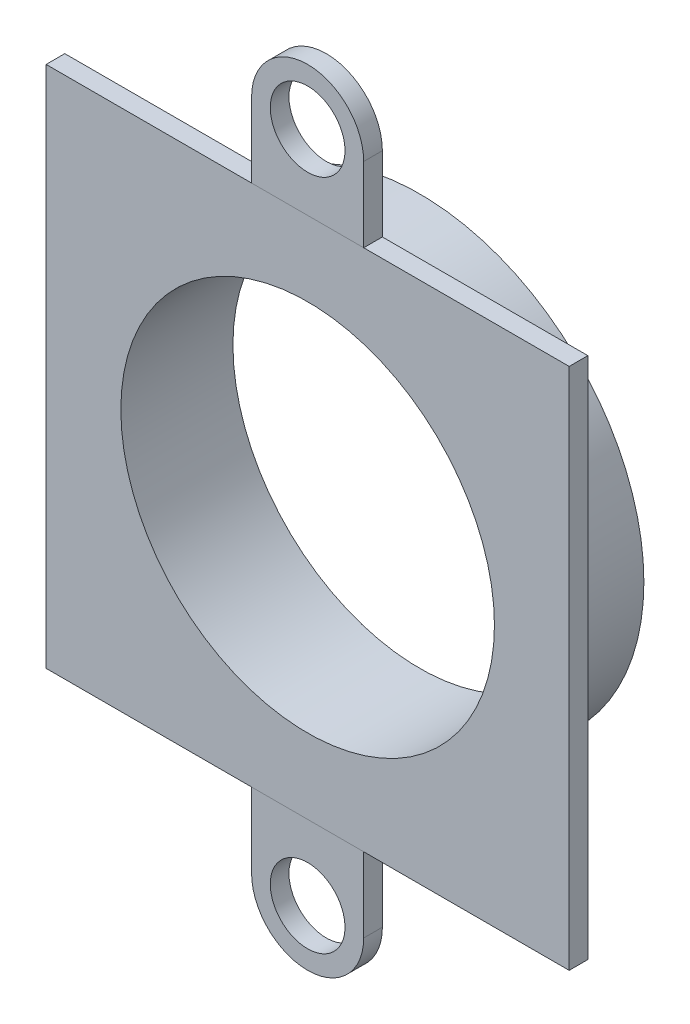
SolidWorks part; units mm, degrees
ref_plane "前视基准面" through (0, 0, 0) normal (0, 0, 1) x (1, 0, 0)
ref_plane "上视基准面" through (0, 0, 0) normal (0, 1, 0) x (1, 0, 0)
ref_plane "右视基准面" through (0, 0, 0) normal (1, 0, 0) x (0, 0, -1)
sketch "草图2" plane through (0, 0, 0) normal (0, 0, 1) x (1, 0, 0)
  line L5 (7, -7) -> (-7, -7)
  line L6 (7, -7) -> (7, 7)
  line L7 (7, 7) -> (-7, 7)
  line L8 (-7, -7) -> (-7, 7)
  line L9 (7, -7) -> (-7, 7) construction
  line L10 (7, 7) -> (-7, -7) construction
  circle A0 centre (0, 0) radius 5
  point P0 (0, 0)
  dimension "D1" = 14
  dimension "D2" = 14
extrude "凸台-拉伸1" add sketch "草图2" along normal blind 0.5
sketch "草图3" plane through (0, -7, 0) normal (0, -1, 0) x (1, 0, 0)
  line L1 (-1.5, 0.5) -> (1.5, 0.5)
  line L2 (-1.5, 0.5) -> (-1.5, 0)
  line L3 (-1.5, 0) -> (1.5, 0)
  line L4 (1.5, 0.5) -> (1.5, 0)
  line L5 (-1.5, 0.5) -> (1.5, 0) construction
  line L6 (-1.5, 0) -> (1.5, 0.5) construction
  line L9 (-7, 0) -> (7, 0) construction
  line L10 (-7, 0.5) -> (7, 0.5) construction
  point P0 (0, 0.25)
  dimension "D1" = 3
extrude "凸台-拉伸2" add sketch "草图3" along normal blind 3.5 separate body
sketch "草图4" plane through (0, 0, 0) normal (0, 0, -1) x (-1, 0, 0)
  line L0 (1.5, -10.5) -> (1.5, -7) construction
  line L1 (1.5, -10.5) -> (-1.5, -10.5) construction
  line L2 (-1.5, -10.5) -> (-1.5, -7) construction
  line L3 (1.5, -9) -> (1.5, -10.5)
  line L4 (1.5, -10.5) -> (-1.5, -10.5)
  line L5 (-1.5, -10.5) -> (-1.5, -9)
  circle A0 centre (0, -9) radius 1.5
  line M3 (-1.5, -7) -> (-1.5, -10.5)
  line M4 (-1.5, -10.5) -> (1.5, -10.5)
  line M5 (1.5, -10.5) -> (1.5, -7)
extrude "切除-拉伸1" cut sketch "草图4" against normal blind 4 contours A0 L4 M5 | A0 M3 M4
sketch "草图5" plane through (0, 0, 0) normal (0, 0, -1) x (-1, 0, 0)
  circle A0 centre (0, -9) radius 1
  dimension "D1" = 2
  dimension "D2" = 9
extrude "切除-拉伸2" cut sketch "草图5" against normal blind 4
mirror "镜向7" about plane through (0, 0, 0) normal (0, 1, 0) of bodies 109
sketch "草图6" plane through (0, 0, 0) normal (0, 0, -1) x (-1, 0, 0)
  circle A3 centre (0, 0) radius 6
  circle A4 centre (0, 0) radius 6
  circle M6 centre (0, 0) radius 5
  dimension "D1" = 1
extrude "凸台-拉伸3" add sketch "草图6" along normal blind 2.5 contours A4 M6
